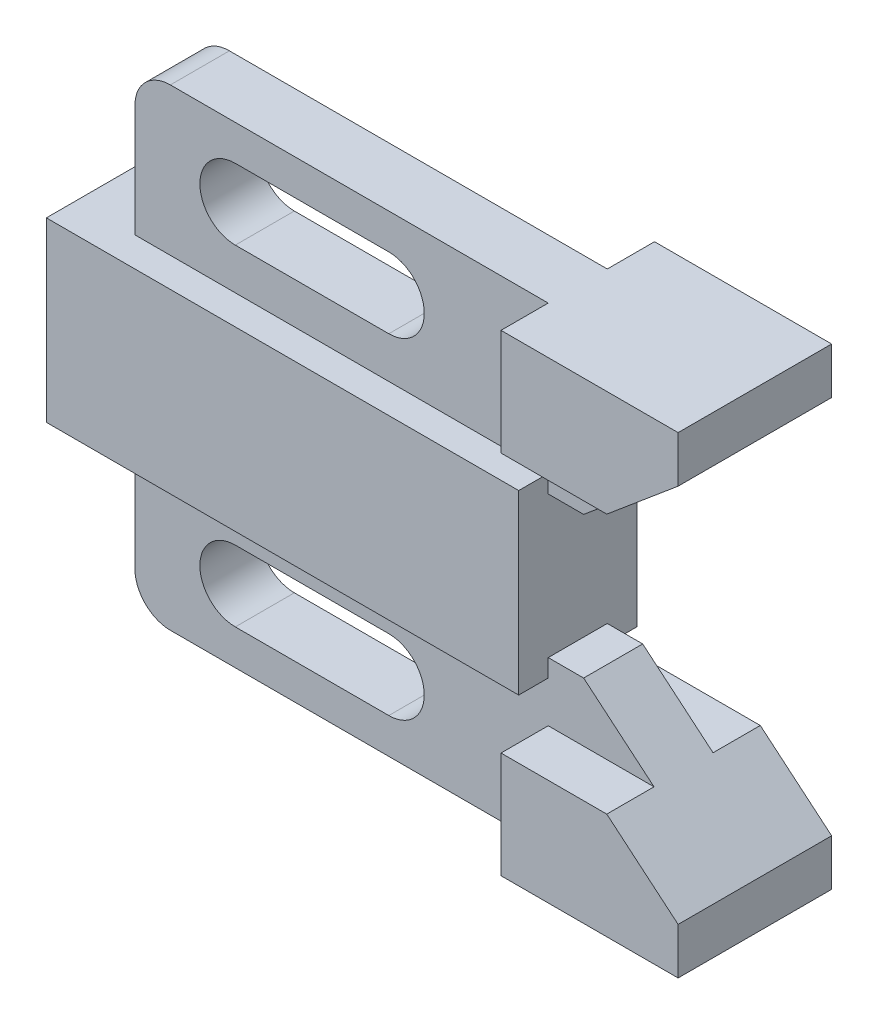
SolidWorks part; units mm, degrees
ref_plane "Front Plane" through (0, 0, 0) normal (0, 0, 1) x (1, 0, 0)
ref_plane "Top Plane" through (0, 0, 0) normal (0, 1, 0) x (1, 0, 0)
ref_plane "Right Plane" through (0, 0, 0) normal (1, 0, 0) x (0, 0, -1)
sketch "Sketch1" plane through (0, 0, 0) normal (0, 0, 1) x (1, 0, 0)
  line L0 (0, 0) -> (250, 0)
  line L1 (250, 0) -> (250, -19.654)
  line L2 (250, -19.654) -> (190, -70)
  line L3 (190, -70) -> (150, -70)
  line L4 (150, -70) -> (150, -130)
  line L5 (150, -130) -> (190, -130)
  line L6 (190, -130) -> (250, -180.346)
  line L7 (250, -180.346) -> (250, -200)
  line L8 (250, -200) -> (0, -200)
  line L9 (0, -200) -> (0, 0)
  line L10 (0, -100) -> (150, -100) construction
  line L11 (42.5, -30) -> (107.5, -30) construction
  line L12 (42.5, -15) -> (107.5, -15)
  line L13 (42.5, -45) -> (107.5, -45)
  line L14 (42.5, -170) -> (107.5, -170) construction
  line L15 (42.5, -185) -> (107.5, -185)
  line L16 (42.5, -155) -> (107.5, -155)
  arc A0 (42.5, -15) -> (42.5, -45) centre (42.5, -30) ccw
  arc A1 (107.5, -45) -> (107.5, -15) centre (107.5, -30) ccw
  arc A2 (42.5, -185) -> (42.5, -155) centre (42.5, -170) cw
  arc A3 (107.5, -155) -> (107.5, -185) centre (107.5, -170) cw
  point P16 (75, -30)
  point P23 (75, -170)
  dimension "D1" = 250
  dimension "D2" = 200
  dimension "D3" = 60
  dimension "JawAngle" = 40
  dimension "D5" = 60
  dimension "D6" = 100
  dimension "SlotLength" = 65
  dimension "SlotWidth" = 30
  dimension "D9" = 30
  dimension "D10" = 75
extrude "Boss-Extrude1" add sketch "Sketch1" along normal mid plane 25
sketch "Sketch3" plane through (0, 0, 0) normal (0, 0, 1) x (1, 0, 0)
  line L0 (175, -100) -> (0, -100) construction
  line L1 (175, -62.5) -> (-25, -62.5)
  line L2 (175, -62.5) -> (175, -137.5)
  line L3 (175, -137.5) -> (-25, -137.5)
  line L4 (-25, -62.5) -> (-25, -137.5)
  line L5 (0, 0) -> (0, -200) construction
  line L6 (150, -130) -> (150, -70) construction
  dimension "D1" = 25
  dimension "D2" = 25
  dimension "D3" = 75
extrude "Boss-Extrude2" add sketch "Sketch3" along normal mid plane 50
sketch "Sketch4" plane through (0, 0, 12.5) normal (0, 0, 1) x (1, 0, 0)
  line L0 (250, 0) -> (0, 0) construction
  line L1 (250, -19.654) -> (250, 0) construction
  line L2 (190, -70) -> (250, -19.654) construction
  line L3 (250, 0) -> (175, 0)
  line L4 (250, -19.654) -> (250, 0)
  line L5 (219.7938, -45) -> (250, -19.654)
  line L6 (219.7938, -45) -> (175, -45)
  line L7 (175, -45) -> (175, 0)
  dimension "ToothLength" = 75
  dimension "ToothWidth" = 45
extrude "Boss-Extrude3" add sketch "Sketch4" along normal blind 20
ref_plane "Plane1" through (0, -100, 0) normal (0, 1, 0) x (1, 0, 0)
mirror "Mirror1" about plane through (0, -100, 0) normal (0, 1, 0) of "Boss-Extrude3"
mirror "Mirror2" about plane through (0, 0, 0) normal (0, 0, 1) of "Mirror1", "Boss-Extrude3"
fillet "Fillet1" [suppressed] radius 5
fillet "Fillet2" radius 15 2 edges at (0, -200, 0) (0, 0, 0)
